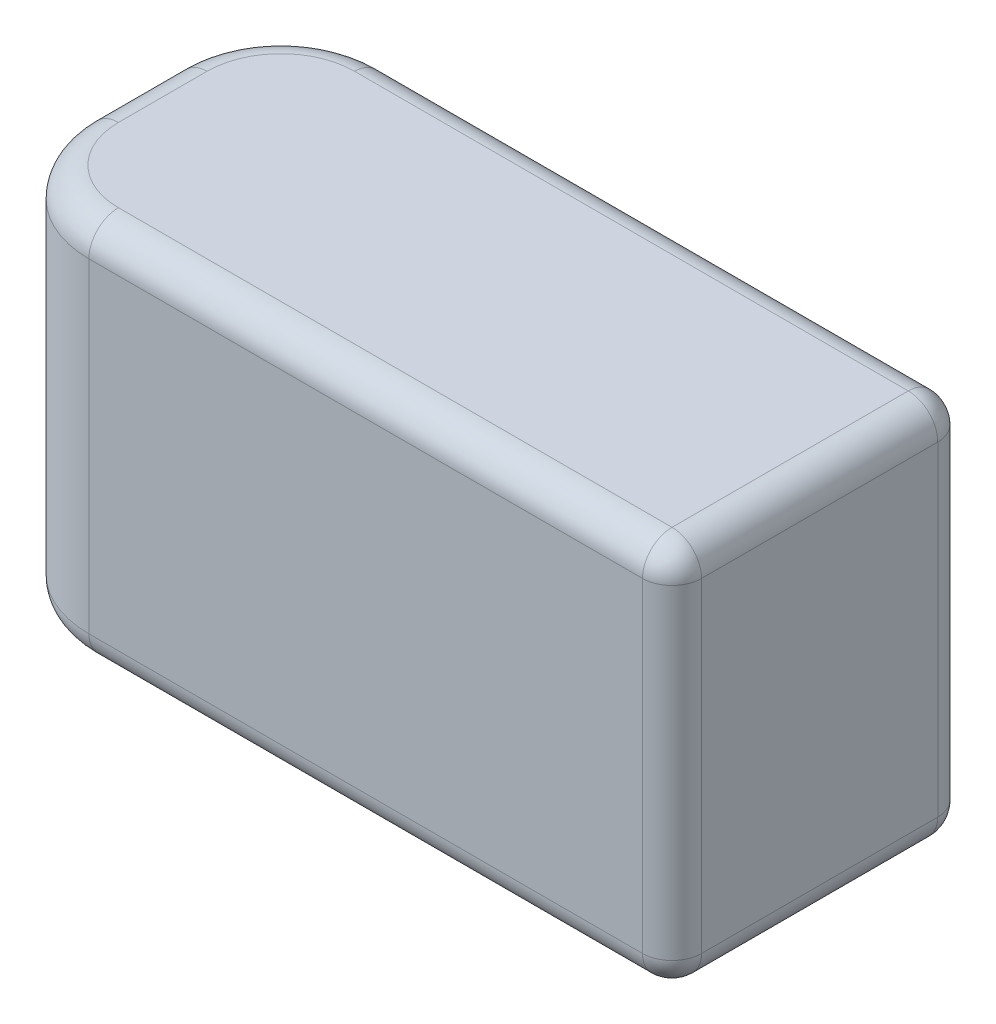
SolidWorks part; units mm, degrees
ref_plane "Front Plane" through (0, 0, 0) normal (0, 0, 1) x (1, 0, 0)
ref_plane "Top Plane" through (0, 0, 0) normal (0, 1, 0) x (1, 0, 0)
ref_plane "Right Plane" through (0, 0, 0) normal (1, 0, 0) x (0, 0, -1)
sketch "Sketch1" plane through (0, 0, 0) normal (0, 0, 1) x (1, 0, 0)
  line L1 (-23.25, -13) -> (23.25, -13)
  line L2 (-23.25, -13) -> (-23.25, 13)
  line L3 (-23.25, 13) -> (23.25, 13)
  line L4 (23.25, -13) -> (23.25, 13)
  line L5 (-23.25, -13) -> (23.25, 13) construction
  line L6 (-23.25, 13) -> (23.25, -13) construction
  point P0 (0, 0)
  dimension "D1" = 26
  dimension "D2" = 46.5
extrude "Boss-Extrude1" add sketch "Sketch1" along normal blind 20
fillet "Fillet1" radius 7 2 edges at (-23.25, 0, 0) (-23.25, 0, 20)
fillet "Fillet2" radius 2 14 edges at (3.5, 13, 0) (-21.1997, 13, 2.0503) (-23.25, 13, 10) (-21.1997, 13, 17.9497) (3.5, -13, 0) (-21.1997, -13, 2.0503) (-23.25, -13, 10) (-21.1997, -13, 17.9497) (23.25, -13, 10) (23.25, 0, 20) (23.25, 13, 10) (23.25, 0, 0) (3.5, 13, 20) (3.5, -13, 20)
